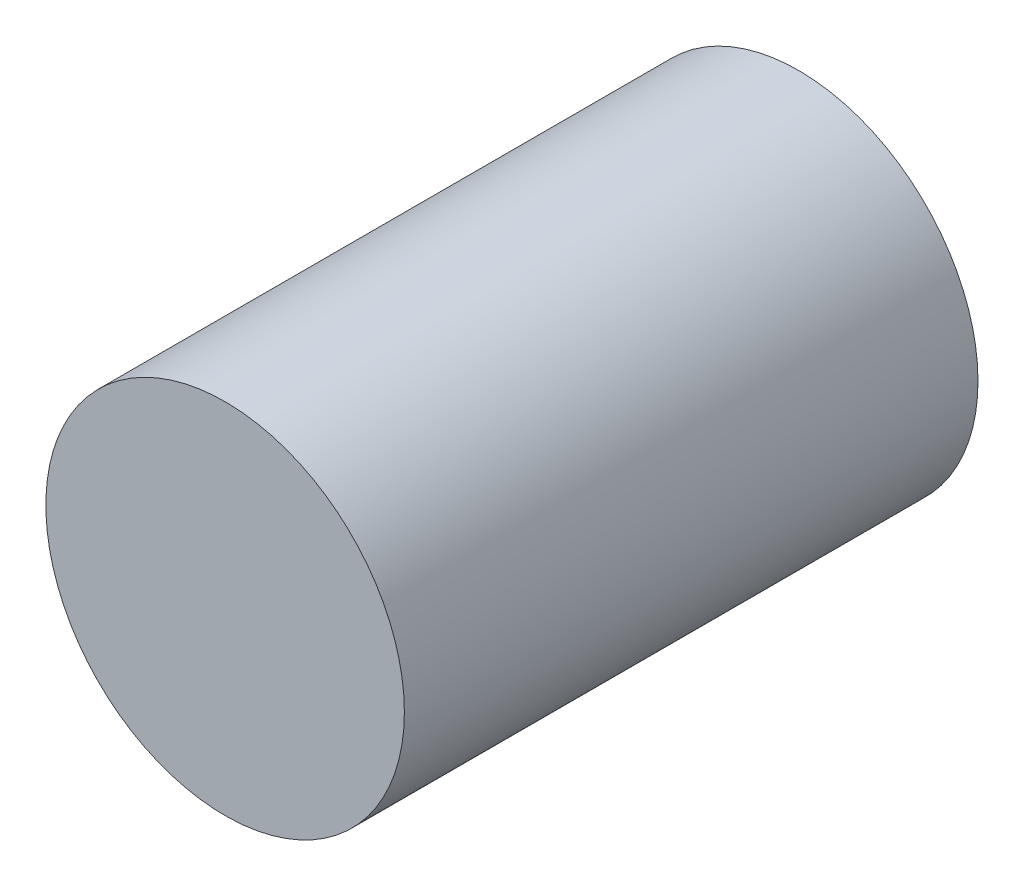
SolidWorks part; units mm, degrees
ref_plane "Front Plane" through (0, 0, 0) normal (0, 0, 1) x (1, 0, 0)
ref_plane "Top Plane" through (0, 0, 0) normal (0, 1, 0) x (1, 0, 0)
ref_plane "Right Plane" through (0, 0, 0) normal (1, 0, 0) x (0, 0, -1)
sketch "Sketch1" plane through (0, 0, 0) normal (0, 0, 1) x (1, 0, 0)
  circle A0 centre (0, 0) radius 12.5
extrude "Boss-Extrude1" add sketch "Sketch1" along normal blind 40
